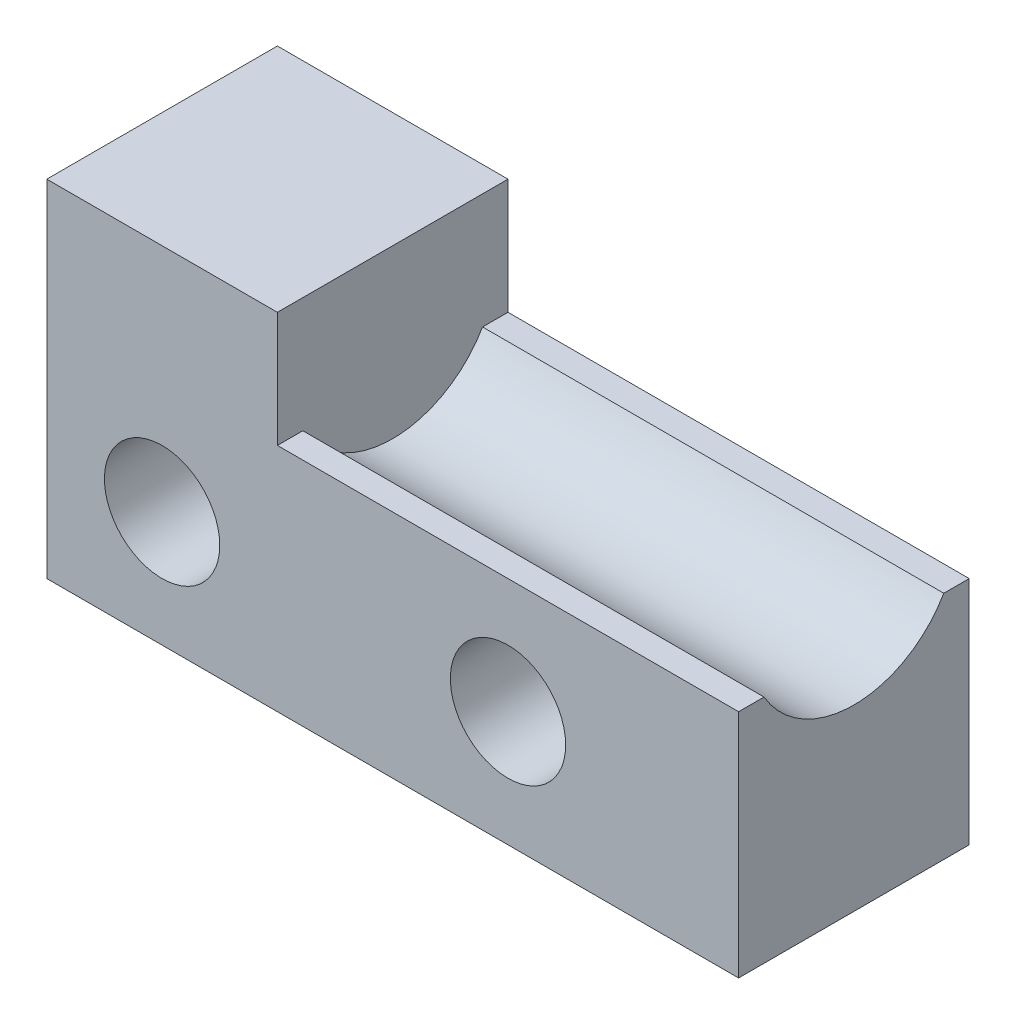
SolidWorks part; units mm, degrees
ref_plane "前基準面" through (0, 0, 0) normal (0, 0, 1) x (1, 0, 0)
ref_plane "上基準面" through (0, 0, 0) normal (0, 1, 0) x (1, 0, 0)
ref_plane "右基準面" through (0, 0, 0) normal (1, 0, 0) x (0, 0, -1)
sketch "草圖1" plane through (0, 0, 0) normal (0, 0, 1) x (1, 0, 0)
  line L0 (0, 0) -> (0, 15)
  line L1 (0, 15) -> (10, 15)
  line L2 (10, 15) -> (10, 10)
  line L3 (10, 10) -> (30, 10)
  line L4 (30, 10) -> (30, 0)
  line L5 (30, 0) -> (0, 0)
  line L6 (30, 5) -> (0, 5) construction
  circle A0 centre (5, 5) radius 2.5
  circle A1 centre (20, 5) radius 2.5
  dimension "D5" = 5
  dimension "D6" = 5
  dimension "D1" = 10
  dimension "D2" = 30
  dimension "D3" = 10
  dimension "D4" = 15
  dimension "D7" = 10
extrude "填料-伸長1" add sketch "草圖1" along normal blind 10
sketch "草圖2" plane through (30, 0, 0) normal (1, 0, 0) x (0, 0, -1)
  line L0 (-5, 15) -> (-5, 0) construction
  line L1 (-10, 15) -> (0, 15) construction
  line L2 (-10, 0) -> (0, 0) construction
  line L3 (-10, 10) -> (0, 10) construction
  circle A0 centre (-5, 12.25) radius 4.5
  dimension "D1" = 9
  dimension "D2" = 2.25
extrude "除料-伸長2" cut sketch "草圖2" against normal up to surface (20 mm away) up to face at (10, 12.5, 5)
